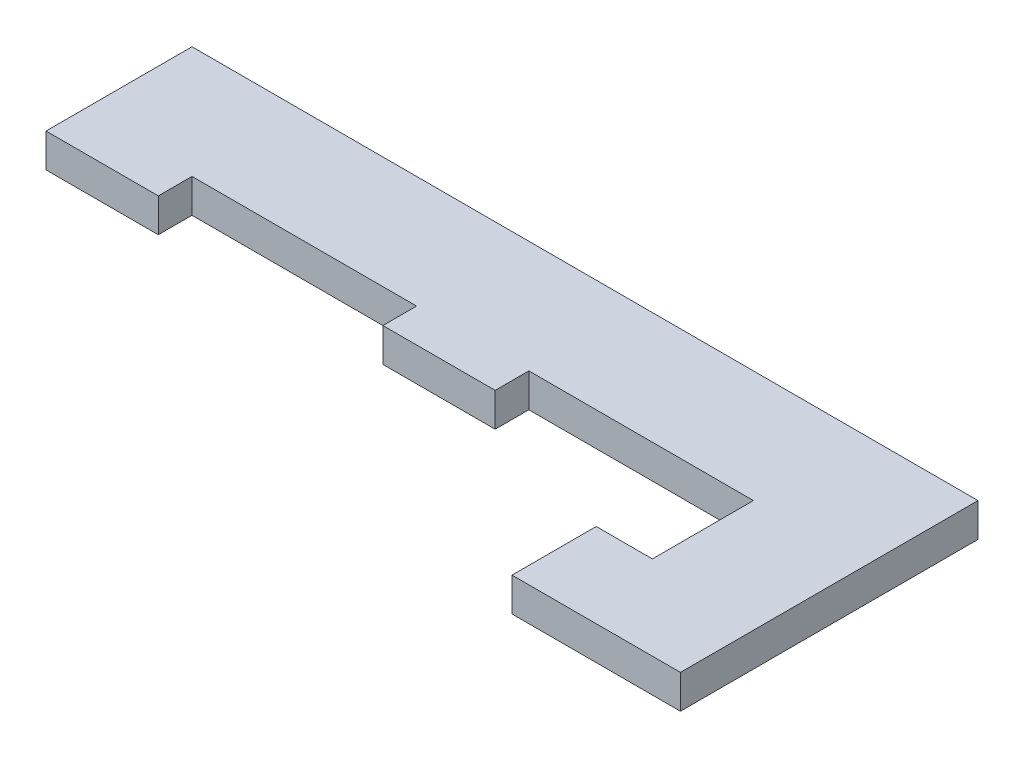
SolidWorks part; units mm, degrees
ref_plane "Front Plane" through (0, 0, 0) normal (0, 0, 1) x (1, 0, 0)
ref_plane "Top Plane" through (0, 0, 0) normal (0, 1, 0) x (1, 0, 0)
ref_plane "Right Plane" through (0, 0, 0) normal (1, 0, 0) x (0, 0, -1)
sketch "Sketch1" plane through (0, 0, 0) normal (0, 1, 0) x (1, 0, 0)
  line L8 (0, -53) -> (0, 0)
  line L9 (0, 0) -> (-140, 0)
  line L15 (-30, -53) -> (0, -53)
  line L17 (-140, -26) -> (-120, -26)
  line L18 (-120, -26) -> (-120, -20)
  line L20 (-140, 0) -> (-140, -26)
  line L21 (-80, -20) -> (-80, -26)
  line L22 (-80, -26) -> (-60, -26)
  line L23 (-60, -26) -> (-60, -20)
  line L24 (-120, -20) -> (-80, -20)
  line L25 (-60, -20) -> (-20, -20)
  line L26 (-30, -53) -> (-30, -38)
  line L27 (-30, -38) -> (-20, -38)
  line L28 (-20, -38) -> (-20, -20)
  point P4 (0, 0)
  dimension "D1" = 10
  dimension "D2" = 20
  dimension "D3" = 30
  dimension "D4" = 20
  dimension "D5" = 6
  dimension "D6" = 30
  dimension "D7" = 40
  dimension "D8" = 18
  dimension "D9" = 15
extrude "Boss-Extrude1" add sketch "Sketch1" along normal blind 6
